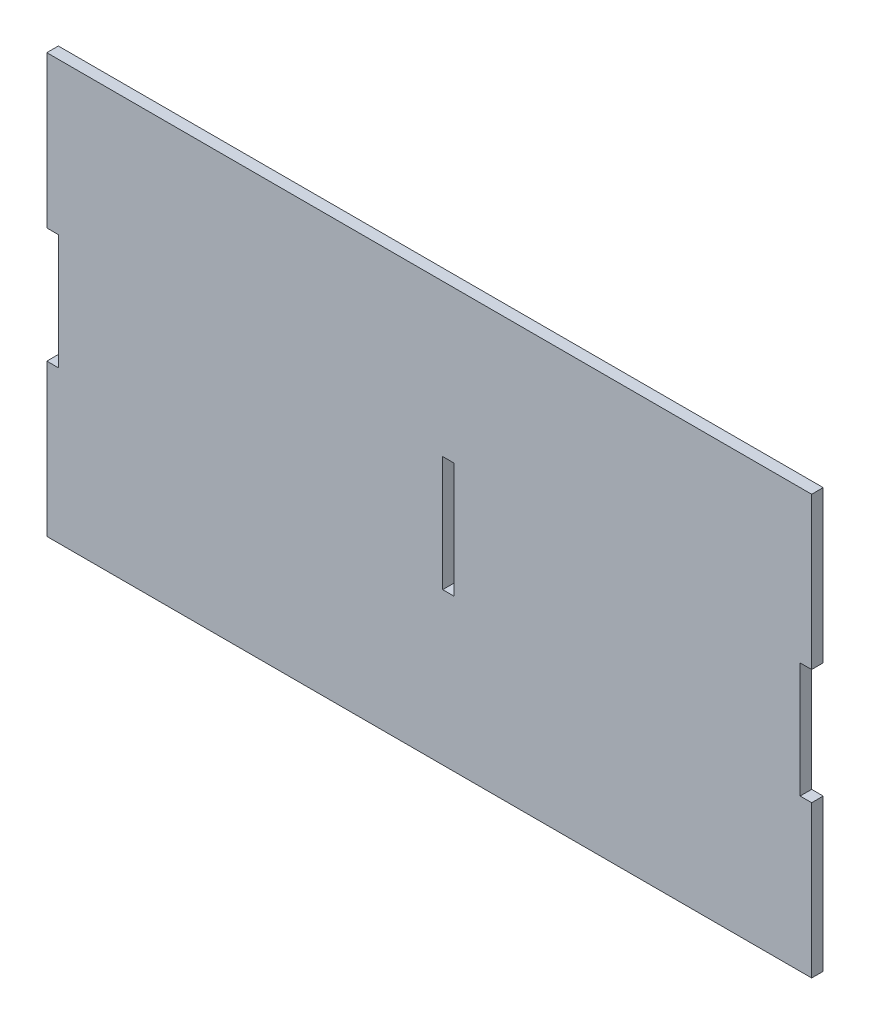
SolidWorks part; units mm, degrees
ref_plane "Front Plane" through (0, 0, 0) normal (0, 0, 1) x (1, 0, 0)
ref_plane "Top Plane" through (0, 0, 0) normal (0, 1, 0) x (1, 0, 0)
ref_plane "Right Plane" through (0, 0, 0) normal (1, 0, 0) x (0, 0, -1)
sketch "Sketch1" plane through (0, 0, 0) normal (0, 0, 1) x (1, 0, 0)
  line L1 (659, 109) -> (858, 109)
  line L3 (858, 0) -> (659, 0)
  line L4 (1244.614, 54.5) -> (659, 54.5) construction
  line L38 (659, 69.5) -> (662, 69.5)
  line L40 (659, 39.5) -> (662, 39.5)
  line L41 (662, 69.5) -> (662, 39.5)
  line L42 (762, 69.5) -> (765, 69.5)
  line L43 (762, 69.5) -> (762, 39.5)
  line L44 (762, 39.5) -> (765, 39.5)
  line L45 (765, 69.5) -> (765, 39.5)
  line L46 (855, 69.5) -> (858, 69.5)
  line L47 (855, 69.5) -> (855, 39.5)
  line L48 (855, 39.5) -> (858, 39.5)
  line L53 (858, 69.5) -> (858, 109)
  line L54 (858, 39.5) -> (858, 0)
  line L57 (659, 69.5) -> (659, 109)
  line L62 (659, 39.5) -> (659, 0)
  dimension "D27" = 3
  dimension "D28" = 30
  dimension "D29" = 3
  dimension "D30" = 30
  dimension "D31" = 100
  dimension "D32" = 90
  dimension "D33" = 3
  dimension "D34" = 30
extrude "Boss-Extrude1" add sketch "Sketch1" along normal blind 3 contours L3 L1
